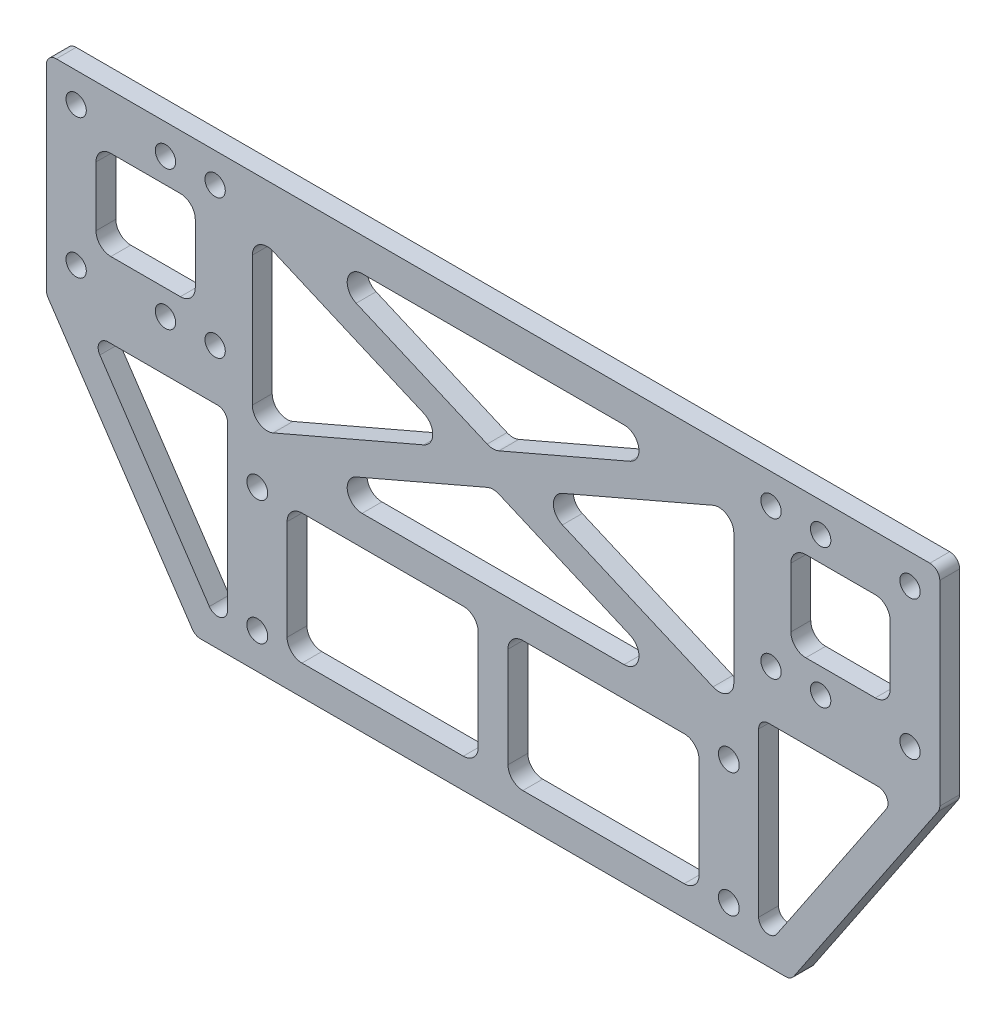
SolidWorks part; units mm, degrees
material "Thornel Mat VMA"
ref_plane "前视基准面" through (0, 0, 0) normal (0, 0, 1) x (1, 0, 0)
ref_plane "上视基准面" through (0, 0, 0) normal (0, 1, 0) x (1, 0, 0)
ref_plane "右视基准面" through (0, 0, 0) normal (1, 0, 0) x (0, 0, -1)
sketch "草图1" plane through (0, 0, 0) normal (0, 0, 1) x (1, 0, 0)
  line L1 (-60, -47.5) -> (60, -47.5)
  line L2 (-60, -47.5) -> (-60, 47.5)
  line L3 (-60, 47.5) -> (60, 47.5)
  line L4 (60, -47.5) -> (60, 47.5)
  line L5 (-60, -47.5) -> (60, 47.5) construction
  line L6 (-60, 47.5) -> (60, -47.5) construction
  point P0 (0, 0)
  dimension "D1" = 120
  dimension "D2" = 95
extrude "凸台-拉伸1" add sketch "草图1" along normal blind 4
sketch "草图2" plane through (0, 0, 0) normal (0, 0, -1) x (-1, 0, 0)
  line L0 (0, 0) -> (0, -47.5) construction
  line L1 (60, -47.5) -> (-60, -47.5) construction
  line L2 (-47.5, -15.3263) -> (0, -15.3263) construction
  line L3 (-47.5, -40.3263) -> (0, -40.3263) construction
  circle A1 centre (47.5, -40.3263) radius 2.1
  circle A3 centre (47.5, -15.3263) radius 2.1
  circle A4 centre (-47.5, -15.3263) radius 2.1
  circle A5 centre (-47.5, -40.3263) radius 2.1
  dimension "D1" = 4.2
  dimension "D2" = 15.3263
  dimension "D3" = 25
  dimension "D4" = 47.5
  dimension "D5" = 47.5
extrude "切除-拉伸1" cut sketch "草图2" against normal blind 10
sketch "草图3" plane through (0, 0, 0) normal (0, 0, -1) x (-1, 0, 0)
  line L1 (-56, 5.1737) -> (56, 5.1737) construction
  line L2 (-56, 5.1737) -> (-56, 33.1737) construction
  line L3 (-56, 33.1737) -> (56, 33.1737) construction
  line L4 (56, 5.1737) -> (56, 33.1737) construction
  line L5 (-56, 5.1737) -> (56, 33.1737) construction
  line L6 (-56, 33.1737) -> (56, 5.1737) construction
  circle A0 centre (56, 33.1737) radius 2.05
  circle A1 centre (-56, 33.1737) radius 2.05
  circle A2 centre (-56, 5.1737) radius 2.05
  circle A3 centre (56, 5.1737) radius 2.05
  point P0 (0, 19.1737)
  dimension "D5" = 4.1
  dimension "D1" = 5.1737
  dimension "D2" = 112
  dimension "D4" = 28
extrude "切除-拉伸2" cut sketch "草图3" against normal blind 10
sketch "草图4" plane through (0, 0, 0) normal (0, 0, -1) x (-1, 0, 0)
  line L0 (-60, 47.5) -> (60, 47.5) construction
  line L1 (-90, -2.8263) -> (90, -2.8263)
  line L2 (-90, -2.8263) -> (-90, 47.5)
  line L3 (-90, 47.5) -> (90, 47.5)
  line L4 (90, -2.8263) -> (90, 47.5)
  line L5 (0, 0) -> (0, 47.5) construction
  circle A0 centre (56, 5.1737) radius 2.05 construction
  circle A1 centre (-56, 33.1737) radius 2.05 construction
  circle A2 centre (-56, 5.1737) radius 2.05 construction
  circle A3 centre (56, 33.1737) radius 2.05 construction
  circle A4 centre (56, 5.1737) radius 2.05
  circle A5 centre (56, 33.1737) radius 2.05
  circle A6 centre (-56, 5.1737) radius 2.05
  circle A7 centre (-56, 33.1737) radius 2.05
  dimension "D1" = 8
  dimension "D2" = 180
extrude "凸台-拉伸2" add sketch "草图4" against normal up to surface (4 mm away) up to face at (-58.05, 5.1737, 4)
sketch "草图5" plane through (0, 0, 0) normal (0, 0, -1) x (-1, 0, 0)
  line L0 (-90, -2.8263) -> (-60, -47.5)
  line L1 (-60, -47.5) -> (-60, -2.8263)
  line L2 (-60, -2.8263) -> (-90, -2.8263)
  line L3 (60, -47.5) -> (60, -2.8263)
  line L4 (60, -2.8263) -> (90, -2.8263)
  line L5 (90, -2.8263) -> (60, -47.5)
extrude "凸台-拉伸3" add sketch "草图5" against normal up to surface (4 mm away) up to face at (45.4, -40.3263, 4)
sketch "草图6" plane through (0, 0, 4) normal (0, 0, 1) x (1, 0, 0)
  line L0 (-81.3129, -5) -> (-53.5, -5)
  line L1 (-53.5, -5) -> (-53.5, -46.4169)
  line L2 (-53.5, -46.4169) -> (-81.3129, -5)
  line L3 (-90, -2.8263) -> (-60, -47.5) construction
  line L4 (0, 0) -> (-90, 0) construction
  line L5 (-90, 47.5) -> (-90, -2.8263) construction
  line L6 (0, 0) -> (0, -47.5) construction
  line L7 (-60, -47.5) -> (60, -47.5) construction
  line L8 (53.5, -46.4169) -> (81.3129, -5)
  line L9 (53.5, -5) -> (53.5, -46.4169)
  line L10 (81.3129, -5) -> (53.5, -5)
  circle A0 centre (-47.5, -15.3263) radius 2.1 construction
  dimension "D1" = 6
  dimension "D2" = 6
  dimension "D3" = 5
extrude "切除-拉伸3" cut sketch "草图6" against normal blind 10
fillet "圆角1" radius 2 6 edges at (81.3129, -5, 2) (53.5, -46.4169, 2) (53.5, -5, 2) (-53.5, -5, 2) (-81.3129, -5, 2) (-53.5, -46.4169, 2)
sketch "草图7" plane through (0, 0, 4) normal (0, 0, 1) x (1, 0, 0)
  line L0 (-56, 33.1737) -> (-84, 33.1737) construction
  line L1 (-56, 5.1737) -> (-84, 5.1737) construction
  line L2 (0, 47.5) -> (0, 0) construction
  line L3 (90, 47.5) -> (-90, 47.5) construction
  circle A0 centre (-84, 33.1737) radius 2.05
  circle A1 centre (-56, 33.1737) radius 2.05 construction
  circle A2 centre (-84, 5.1737) radius 2.05
  circle A3 centre (84, 33.1737) radius 2.05
  circle A4 centre (84, 5.1737) radius 2.05
  dimension "D1" = 28
extrude "切除-拉伸4" cut sketch "草图7" against normal blind 10
fillet "圆角2" radius 2 6 edges at (-90, -2.8263, 2) (-90, 47.5, 2) (90, 47.5, 2) (90, -2.8263, 2) (60, -47.5, 2) (-60, -47.5, 2)
sketch "草图8" plane through (0, 0, 4) normal (0, 0, 1) x (1, 0, 0)
  line L0 (0, 0) -> (0, 60.1615) construction
  line L1 (-80, 10.1737) -> (-60, 10.1737)
  line L2 (-80, 10.1737) -> (-80, 28.1737)
  line L3 (-80, 28.1737) -> (-60, 28.1737)
  line L4 (-60, 10.1737) -> (-60, 28.1737)
  line L5 (-80, 10.1737) -> (-60, 28.1737) construction
  line L6 (-80, 28.1737) -> (-60, 10.1737) construction
  line L7 (80, 28.1737) -> (60, 10.1737) construction
  line L8 (80, 10.1737) -> (60, 28.1737) construction
  line L9 (60, 10.1737) -> (60, 28.1737)
  line L10 (80, 28.1737) -> (60, 28.1737)
  line L11 (80, 10.1737) -> (80, 28.1737)
  line L12 (80, 10.1737) -> (60, 10.1737)
  line L13 (88, 47.5) -> (-88, 47.5) construction
  line L14 (-48.5, -9.3263) -> (48.5, -9.3263)
  line L15 (-48.5, -9.3263) -> (-48.5, 32.5)
  line L16 (-48.5, 32.5) -> (48.5, 32.5)
  line L17 (48.5, -9.3263) -> (48.5, 32.5)
  line L18 (-48.5, -9.3263) -> (48.5, 32.5) construction
  line L19 (-48.5, 32.5) -> (48.5, -9.3263) construction
  line L20 (-53.5, -39.8512) -> (-53.5, -7) construction
  line L21 (-49.6879, 29.7452) -> (47.3121, -12.0811)
  line L22 (-47.3121, -12.0811) -> (49.6879, 29.7452)
  line L23 (-47.3121, 35.2548) -> (49.6879, -6.5715)
  line L24 (-49.6879, -6.5715) -> (47.3121, 35.2548)
  circle A0 centre (-56, 33.1737) radius 2.05 construction
  circle A1 centre (-84, 33.1737) radius 2.05 construction
  circle A3 centre (-84, 5.1737) radius 2.05 construction
  circle A4 centre (47.5, -15.3263) radius 2.1 construction
  point P0 (-70, 19.1737)
  point P20 (70, 19.1737)
  point P21 (0, 11.5869)
  dimension "D1" = 5
  dimension "D2" = 4
  dimension "D3" = 20
  dimension "D4" = 5
  dimension "D5" = 15
  dimension "D6" = 5
  dimension "D7" = 6
  dimension "D8" = 3
  dimension "D9" = 3
extrude "切除-拉伸5" cut sketch "草图8" against normal blind 10 contours L1 L4 L3 L2 | L15 L24 L21 | L23 L24 L16 | L22 L23 L17 | L22 L14 L21 | L12 L11 L10 L9
sketch "草图9" plane through (0, 0, 4) normal (0, 0, 1) x (1, 0, 0)
  line L0 (0, 0) -> (0, -28.4131) construction
  line L1 (-41.5, -41.5) -> (41.5, -41.5)
  line L2 (-41.5, -41.5) -> (-41.5, -15.3263)
  line L3 (-41.5, -15.3263) -> (41.5, -15.3263)
  line L4 (41.5, -41.5) -> (41.5, -15.3263)
  line L5 (-41.5, -41.5) -> (41.5, -15.3263) construction
  line L6 (-41.5, -15.3263) -> (41.5, -41.5) construction
  line L7 (-58.934, -47.5) -> (58.934, -47.5) construction
  line L8 (-40.9234, -9.3263) -> (40.9234, -9.3263) construction
  line L9 (0, -15.3263) -> (0, -41.5) construction
  line L10 (-3, -15.3263) -> (-3, -41.5)
  line L11 (3, -15.3263) -> (3, -41.5)
  circle A0 centre (47.5, -15.3263) radius 2.1 construction
  point P0 (0, -28.4131)
  dimension "D1" = 6
  dimension "D2" = 6
  dimension "D3" = 6
  dimension "D4" = 3
  dimension "D5" = 3
extrude "切除-拉伸6" cut sketch "草图9" against normal blind 10 contours L10 L3 L2 L1 | L3 L11 L1 L4
fillet "圆角3" radius 3 28 edges at (-41.5, -41.5, 2) (-41.5, -15.3263, 2) (-3, -15.3263, 2) (-3, -41.5, 2) (41.5, -41.5, 2) (3, -41.5, 2) (3, -15.3263, 2) (41.5, -15.3263, 2) (48.5, -6.0593, 2) (7.5766, 11.5869, 2) (48.5, 29.233, 2) (40.9234, -9.3263, 2) (-40.9234, -9.3263, 2) (0, 8.3198, 2) (-7.5766, 11.5869, 2) (-48.5, -6.0593, 2) (-48.5, 29.233, 2) (60, 28.1737, 2) (80, 28.1737, 2) (80, 10.1737, 2) (60, 10.1737, 2) (-40.9234, 32.5, 2) (40.9234, 32.5, 2) (0, 14.8539, 2) (-80, 28.1737, 2) (-60, 28.1737, 2) (-80, 10.1737, 2) (-60, 10.1737, 2)
sketch "草图10" plane through (0, 0, 4) normal (0, 0, 1) x (1, 0, 0)
  line L0 (0, -27.7546) -> (0, 58.8106) construction
  line L1 (-84, 33.1737) -> (-66, 33.1737) construction
  line L2 (-84, 33.1737) -> (-84, 5.1737) construction
  line L3 (-84, 5.1737) -> (-66, 5.1737) construction
  line L4 (-66, 33.1737) -> (-66, 5.1737) construction
  circle A0 centre (-66, 33.1737) radius 2.05
  circle A1 centre (-66, 5.1737) radius 2.05
  circle A2 centre (-84, 5.1737) radius 2.05 construction
  circle A3 centre (-84, 5.1737) radius 2.05 construction
  circle A4 centre (66, 5.1737) radius 2.05
  circle A5 centre (66, 33.1737) radius 2.05
  dimension "D1" = 18
extrude "切除-拉伸7" cut sketch "草图10" against normal blind 10
sketch "草图11" plane through (0, 0, 4) normal (0, 0, 1) x (1, 0, 0)
  line L0 (-90, 45.5) -> (-90, -2.2171) construction
  line L1 (-90, 39.1737) -> (90, 39.1737)
  line L2 (-90, 39.1737) -> (-90, 54.1737)
  line L3 (-90, 54.1737) -> (90, 54.1737)
  line L4 (90, 39.1737) -> (90, 54.1737)
  line L5 (90, -2.2171) -> (90, 45.5) construction
  circle A0 centre (84, 33.1737) radius 2.05 construction
  dimension "D1" = 6
  dimension "D2" = 15
extrude "切除-拉伸8" cut sketch "草图11" against normal blind 10
fillet "圆角4" radius 2 2 edges at (-90, 39.1737, 2) (90, 39.1737, 2)
